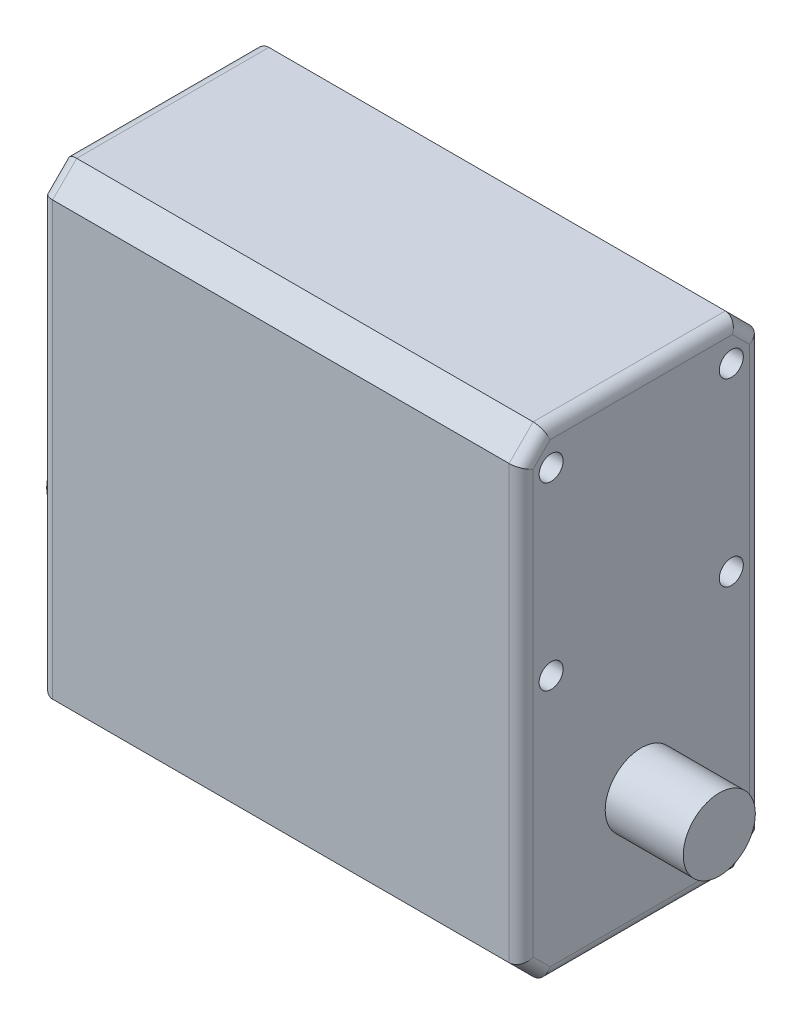
SolidWorks part; units mm, degrees
ref_plane "正面" through (0, 0, 0) normal (0, 0, 1) x (1, 0, 0)
ref_plane "平面" through (0, 0, 0) normal (0, 1, 0) x (1, 0, 0)
ref_plane "右側面" through (0, 0, 0) normal (1, 0, 0) x (0, 0, -1)
sketch "ｽｹｯﾁ1" plane through (0, 0, 0) normal (1, 0, 0) x (0, 0, -1)
  line L1 (-6.5181, 29.2479) -> (-26.5181, 29.2479)
  line L2 (-6.5181, 29.2479) -> (-6.5181, -10.7521)
  line L3 (-6.5181, -10.7521) -> (-26.5181, -10.7521)
  line L4 (-26.5181, 29.2479) -> (-26.5181, -10.7521)
extrude "ﾎﾞｽ - 押し出し1" add sketch "ｽｹｯﾁ1" along normal blind 40
sketch "ｽｹｯﾁ2" plane through (0, 0, 0) normal (-1, 0, 0) x (0, 0, 1)
  line L6 (26.5181, -10.7521) -> (6.5181, -10.7521) construction
  line L7 (16.5181, -10.7521) -> (16.5181, -0.7521)
  circle A0 centre (9.0181, 26.2015) radius 1
  circle A1 centre (9.0181, 11.2015) radius 1
  circle A2 centre (24.0181, 11.2015) radius 1
  circle A3 centre (24.0181, 26.2015) radius 1
extrude "ｶｯﾄ - 押し出し3" cut sketch "ｽｹｯﾁ2" against normal blind 40 contours A0 | A1 | A2 | A3
ref_plane "平面1" through (0, 0, 0) normal (-1, 0, 0) x (0, 0, 1)
sketch "ｽｹｯﾁ4" plane through (0, 0, 0) normal (-1, 0, 0) x (0, 0, 1)
  line L0 (6.5181, -10.7521) -> (26.5181, 29.2479)
  line L1 (6.5181, 29.2479) -> (26.5181, -10.7521)
  line L3 (26.5181, -10.7521) -> (6.5181, -10.7521) construction
  line L4 (16.5181, -10.7521) -> (16.5181, -0.7521)
  circle A0 centre (16.5181, -0.7521) radius 1.5
extrude "ﾎﾞｽ - 押し出し2" add sketch "ｽｹｯﾁ4" along normal blind 5 and the other way blind 45
chamfer "面取り1" distance 2 angle 45 4 edges at (20, 29.2479, 26.5181) (20, 29.2479, 6.5181) (20, -10.7521, 6.5181) (20, -10.7521, 26.5181)
fillet "ﾌｨﾚｯﾄ1" radius 1 16 edges at (0, 28.2479, 25.5181) (0, 29.2479, 16.5181) (0, 28.2479, 7.5181) (0, 9.2479, 6.5181) (0, -9.7521, 7.5181) (0, -10.7521, 16.5181) (0, -9.7521, 25.5181) (0, 9.2479, 26.5181) (40, -9.7521, 7.5181) (40, -10.7521, 16.5181) (40, -9.7521, 25.5181) (40, 9.2479, 26.5181) (40, 28.2479, 25.5181) (40, 29.2479, 16.5181) (40, 28.2479, 7.5181) (40, 9.2479, 6.5181)
sketch "ｽｹｯﾁ5" plane through (-5, 0, 0) normal (-1, 0, 0) x (0, 0, 1)
  circle A0 centre (16.5181, -0.7521) radius 3
extrude "ﾎﾞｽ - 押し出し3" add sketch "ｽｹｯﾁ5" against normal blind 50
ref_plane "平面2" through (-5, 0, 0) normal (-1, 0, 0) x (0, 0, 1)
sketch "ｽｹｯﾁ7" plane through (-5, 0, 0) normal (-1, 0, 0) x (0, 0, 1)
  circle A0 centre (16.5181, -0.7521) radius 3
extrude "ﾎﾞｽ - 押し出し4" add sketch "ｽｹｯﾁ7" along normal blind 1.5 and the other way blind 53
sketch "ｽｹｯﾁ12" plane through (0, 0, 0) normal (0, 0, 1) x (1, 0, 0)
  line L0 (48, -3.7521) -> (48, 2.2479) construction
  line L1 (48, 3.104) -> (46.5, 3.104)
  line L2 (48, 3.104) -> (48, -3.7521)
  line L3 (48, -3.7521) -> (46.5, -3.7521)
  line L4 (46.5, 3.104) -> (46.5, -3.7521)
  line L5 (40, -3.7521) -> (48, -3.7521) construction
  dimension "D1" = 1.5
extrude "ｶｯﾄ - 押し出し6" cut sketch "ｽｹｯﾁ12" along normal blind 25.5
ref_plane "平面3" through (-6.5, 0, 0) normal (-1, 0, 0) x (0, 0, 1)
ref_plane "平面4" through (0, 0, 0) normal (-1, 0, 0) x (0, 0, 1)
sketch "ｽｹｯﾁ9" plane through (0, 0, 0) normal (-1, 0, 0) x (0, 0, 1)
  circle A0 centre (16.5181, -0.7521) radius 3
extrude "ﾎﾞｽ - 押し出し7" add sketch "ｽｹｯﾁ9" along normal blind 6.5
